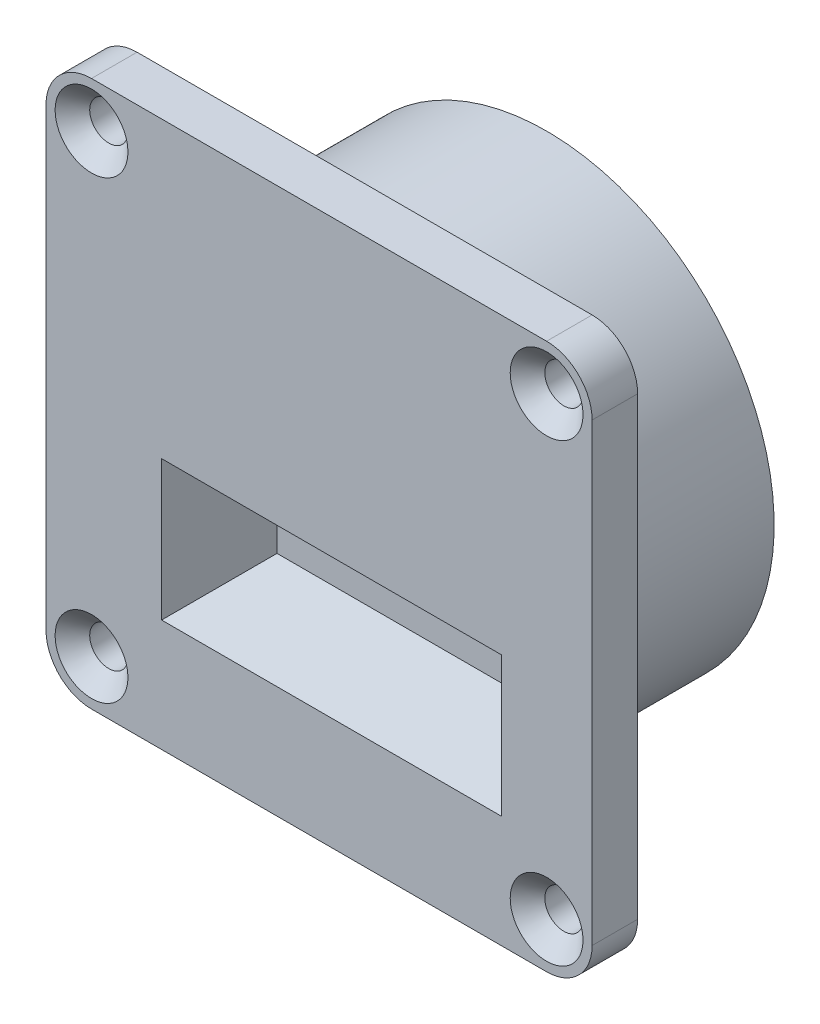
SolidWorks part; units mm, degrees
ref_plane "Спереди" through (0, 0, 0) normal (0, 0, 1) x (1, 0, 0)
ref_plane "Сверху" through (0, 0, 0) normal (0, 1, 0) x (1, 0, 0)
ref_plane "Справа" through (0, 0, 0) normal (1, 0, 0) x (0, 0, -1)
sketch "Эскиз1" plane through (0, 0, 0) normal (0, 0, 1) x (1, 0, 0)
  line L1 (0, 0) -> (60, 0)
  line L2 (0, 0) -> (0, 60)
  line L3 (0, 60) -> (60, 60)
  line L4 (60, 0) -> (60, 60)
  dimension "D1" = 60
  dimension "D2" = 60
extrude "Вытянуть1" add sketch "Эскиз1" along normal blind 5
sketch "Эскиз2" plane through (0, 0, 0) normal (0, 0, -1) x (-1, 0, 0)
  line L0 (-60, 30) -> (0, 30) construction
  line L1 (-30, 60) -> (-30, 0) construction
  line L2 (-60, 60) -> (0, 60) construction
  line L3 (0, 0) -> (-60, 0) construction
  line L4 (-60, 0) -> (-60, 60) construction
  line L5 (0, 60) -> (0, 0) construction
  circle A0 centre (-30, 30) radius 25
  dimension "D1" = 50
extrude "Вытянуть2" add sketch "Эскиз2" along normal blind 20
sketch "Эскиз3" plane through (0, 0, -20) normal (0, 0, -1) x (-1, 0, 0)
  line L0 (-30, 52.8919) -> (-30, 5.4321) construction
  line L2 (-41, 17) -> (-40, 17)
  line L3 (-41, 17) -> (-41, 20)
  line L4 (-41, 20) -> (-40, 20)
  line L5 (-40, 17) -> (-40, 20)
  line L6 (-20, 20) -> (-19, 20)
  line L7 (-20, 20) -> (-20, 17)
  line L8 (-20, 17) -> (-19, 17)
  line L9 (-19, 20) -> (-19, 17)
  circle A0 centre (-30, 30) radius 25 construction
  dimension "D5" = 10
  dimension "D6" = 10
  dimension "D1" = 3
  dimension "D2" = 3
  dimension "D3" = 1
  dimension "D4" = 1
  dimension "D7" = 20
  dimension "D8" = 10
extrude "Вытянуть3" add sketch "Эскиз3" along normal blind 8
sketch "Эскиз4" plane through (0, 0, 5) normal (0, 0, 1) x (1, 0, 0)
  line L0 (0, 0) -> (60, 0) construction
  line L1 (15.3784, 15) -> (47.3784, 15)
  line L2 (15.3784, 15) -> (15.3784, 25)
  line L3 (15.3784, 25) -> (47.3784, 25)
  line L4 (47.3784, 15) -> (47.3784, 25)
  dimension "D1" = 10
  dimension "D2" = 32
  dimension "D3" = 15
extrude "Вырез-Вытянуть1" cut sketch "Эскиз4" against normal blind 10
draft "Уклон1" type of draft neutral plane draft angle 15 faces to draft 4 face at (31.3784, 25, 0) face at (47.3784, 20, 0) face at (31.3784, 15, 0) face at (15.3784, 20, 0) neutral plane through (15.3784, 25, -5) neutral plane normal (0, 0, 1) parameters "D1"=15
sketch "Эскиз5" plane through (0, 0, 5) normal (0, 0, 1) x (1, 0, 0)
  line L0 (60, 60) -> (0, 60) construction
  line L1 (0, 60) -> (0, 0) construction
  line L2 (30, 76.7876) -> (30, -8.7142) construction
  line L3 (60, 0) -> (60, 60) construction
  circle A0 centre (5, 55) radius 2.1
  circle A1 centre (55, 55) radius 2.1
  circle A2 centre (55, 5) radius 2.1
  circle A3 centre (5, 5) radius 2.1
  dimension "D2" = 50
  dimension "D4" = 50
  dimension "D5" = 5
  dimension "D7" = 4.2
  dimension "D6" = 5
extrude "Вытянуть4" add sketch "Эскиз5" along normal blind 0.5
sketch "Эскиз6" plane through (0, 0, 5.5) normal (0, 0, 1) x (1, 0, 0)
  circle A1 centre (5, 55) radius 2.1
  circle A2 centre (5, 55) radius 2.1
  dimension "D1" = 0
extrude "Вырез-Вытянуть2" cut sketch "Эскиз6" against normal blind 5.5
sketch "Эскиз7" plane through (0, 0, 5.5) normal (0, 0, 1) x (1, 0, 0)
  circle A1 centre (55, 55) radius 2.1
  circle A2 centre (55, 55) radius 2.1
  dimension "D1" = 0
extrude "Вырез-Вытянуть3" cut sketch "Эскиз7" against normal blind 5.5
sketch "Эскиз8" plane through (0, 0, 5.5) normal (0, 0, 1) x (1, 0, 0)
  circle A1 centre (55, 5) radius 2.1
  circle A2 centre (55, 5) radius 2.1
  dimension "D1" = 0
extrude "Вырез-Вытянуть4" cut sketch "Эскиз8" against normal blind 5.5
sketch "Эскиз9" plane through (0, 0, 5.5) normal (0, 0, 1) x (1, 0, 0)
  circle A1 centre (5, 5) radius 2.1
  circle A2 centre (5, 5) radius 2.1
  dimension "D1" = 0
extrude "Вырез-Вытянуть5" cut sketch "Эскиз9" against normal blind 5.5
fillet "Скругление1" radius 5 4 edges at (0, 0, 2.5) (60, 0, 2.5) (0, 60, 2.5) (60, 60, 2.5)
chamfer "Фаска3" distance 1.9 angle 45 4 edges at (52.9, 5, 5) (2.9, 5, 5) (2.9, 55, 5) (52.9, 55, 5)
sketch "Эскиз11" plane through (0, 0, -20) normal (0, 0, -1) x (-1, 0, 0)
  line L0 (-41, 20) -> (-41, 17) construction
  line L1 (-20, 20) -> (-20, 17) construction
  line L2 (-19, 20) -> (-20, 20) construction
  text T0 "-" font "GOST type B" height 8
  text T1 "+" font "GOST type B" height 8
  text T2 "CBH" font "GOST type B" height 5
  dimension "D1" = 2.5
  dimension "D2" = 2.5
  dimension "D3" = 2.5
  dimension "D4" = 2.5
extrude "Вырез-Вытянуть7" cut sketch "Эскиз11" against normal blind 0.1
